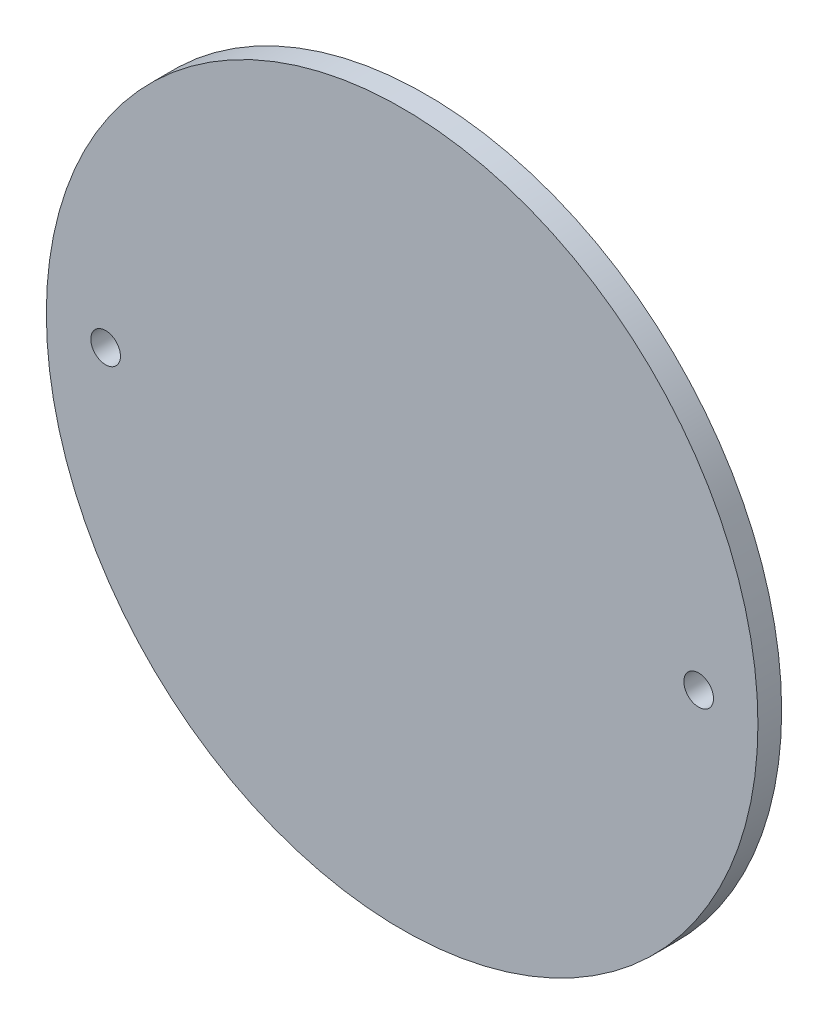
SolidWorks part; units mm, degrees
ref_plane "Plan de face" through (0, 0, 0) normal (0, 0, 1) x (1, 0, 0)
ref_plane "Plan de dessus" through (0, 0, 0) normal (0, 1, 0) x (1, 0, 0)
ref_plane "Plan de droite" through (0, 0, 0) normal (1, 0, 0) x (0, 0, -1)
sketch "Esquisse1" plane through (0, 0, 0) normal (0, 0, 1) x (1, 0, 0)
  circle A0 centre (0, 0) radius 30
  circle A1 centre (25, 0) radius 1.25
  circle A2 centre (-25, 0) radius 1.25
  dimension "D1" = 60
  dimension "D2" = 2.5
  dimension "D3" = 2.5
  dimension "D4" = 50
  dimension "D5" = 25
extrude "Boss.-Extru.1" add sketch "Esquisse1" along normal blind 2
